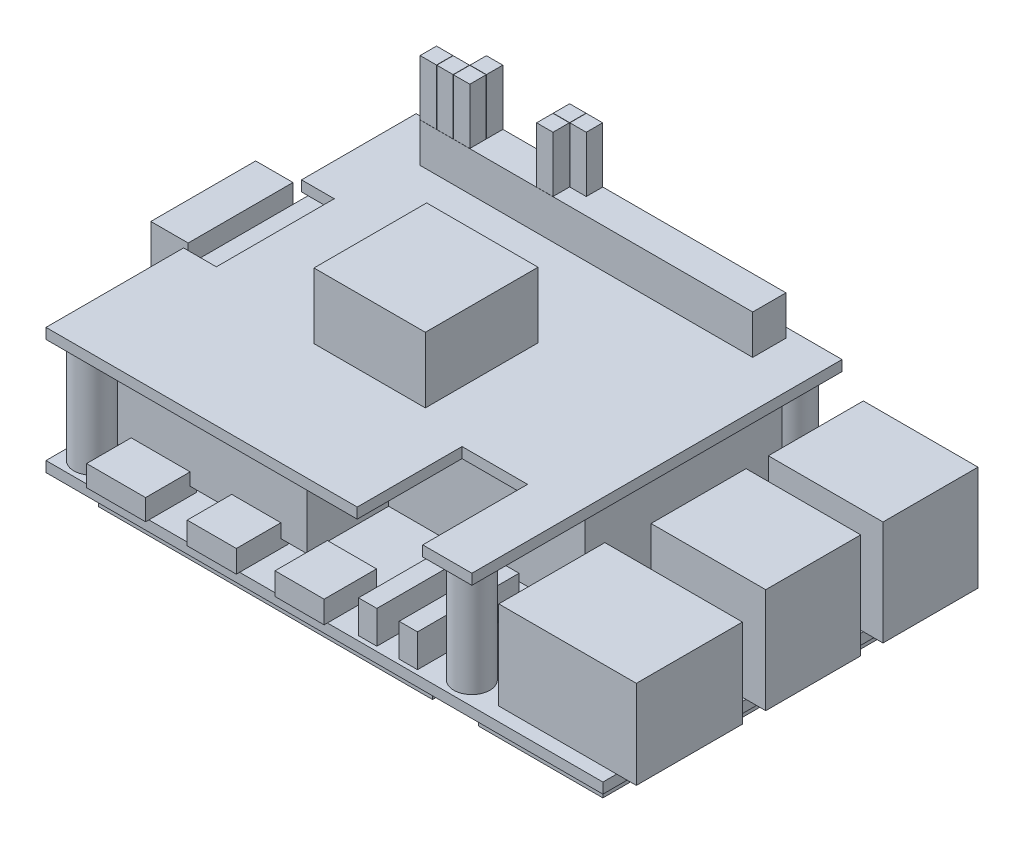
SolidWorks part; units mm, degrees
ref_plane "Front Plane" through (0, 0, 0) normal (0, 0, 1) x (1, 0, 0)
ref_plane "Top Plane" through (0, 0, 0) normal (0, 1, 0) x (1, 0, 0)
ref_plane "Right Plane" through (0, 0, 0) normal (1, 0, 0) x (0, 0, -1)
ref_plane "PZm18" through (0, -18, 0) normal (0, 1, 0) x (1, 0, 0)
sketch "Sketch1" plane through (0, -18, 0) normal (0, 1, 0) x (1, 0, 0)
  line L0 (-55, -92.5) -> (30, -92.5)
  line L1 (30, -92.5) -> (30, -36.5)
  line L2 (30, -36.5) -> (-55, -36.5)
  line L3 (-55, -36.5) -> (-55, -92.5)
extrude "Pi 5 PCB" add sketch "Sketch1" along normal blind 1.6
ref_plane "PZm19_5" through (0, -19.5, 0) normal (0, 1, 0) x (1, 0, 0)
sketch "Sketch2" plane through (0, -19.5, 0) normal (0, 1, 0) x (1, 0, 0)
  line L0 (-48, -91.5) -> (3, -91.5)
  line L1 (3, -91.5) -> (3, -37.5)
  line L2 (3, -37.5) -> (-48, -37.5)
  line L3 (-48, -37.5) -> (-48, -91.5)
extrude "Underside Parts 1" add sketch "Sketch2" along normal blind 1.5
sketch "Sketch3" plane through (0, -19.5, 0) normal (0, 1, 0) x (1, 0, 0)
  line L0 (-54, -85.5) -> (29, -85.5)
  line L1 (29, -85.5) -> (29, -43.5)
  line L2 (29, -43.5) -> (-54, -43.5)
  line L3 (-54, -43.5) -> (-54, -85.5)
extrude "Underside Parts 2" add sketch "Sketch3" along normal blind 1.5
sketch "Sketch4" plane through (0, -19.5, 0) normal (0, 1, 0) x (1, 0, 0)
  line L0 (10, -91.5) -> (29, -91.5)
  line L1 (29, -91.5) -> (29, -37.5)
  line L2 (29, -37.5) -> (10, -37.5)
  line L3 (10, -37.5) -> (10, -91.5)
extrude "Underside Parts 3" add sketch "Sketch4" along normal blind 1.5
sketch "Sketch5" plane through (0, -19.5, 0) normal (0, 1, 0) x (1, 0, 0)
  line L0 (-57.5, -70.5) -> (-41, -70.5)
  line L1 (-41, -70.5) -> (-41, -58.5)
  line L2 (-41, -58.5) -> (-57.5, -58.5)
  line L3 (-57.5, -58.5) -> (-57.5, -70.5)
extrude "microSD Card" add sketch "Sketch5" along normal blind 1.5
ref_plane "PZm15_1" through (0, -15.1, 0) normal (0, 1, 0) x (1, 0, 0)
sketch "Sketch6" plane through (0, -15.1, 0) normal (0, 1, 0) x (1, 0, 0)
  line L0 (-55, -86.2) -> (-21.5, -86.2)
  line L1 (-21.5, -86.2) -> (-21.5, -43.7)
  line L2 (-21.5, -43.7) -> (-55, -43.7)
  line L3 (-55, -43.7) -> (-55, -86.2)
extrude "Cooler Fins" add sketch "Sketch6" along normal blind 13.7
sketch "Sketch7" plane through (0, -15.1, 0) normal (0, 1, 0) x (1, 0, 0)
  line L0 (-21.5, -73.7) -> (8.5, -73.7)
  line L1 (8.5, -73.7) -> (8.5, -43.7)
  line L2 (8.5, -43.7) -> (-21.5, -43.7)
  line L3 (-21.5, -43.7) -> (-21.5, -73.7)
extrude "Cooler Fan" add sketch "Sketch7" along normal blind 13.7
ref_plane "PZm16_4" through (0, -16.4, 0) normal (0, 1, 0) x (1, 0, 0)
sketch "Sketch8" plane through (0, -16.4, 0) normal (0, 1, 0) x (1, 0, 0)
  line L0 (-47.9, -42.54) -> (2.9, -42.54)
  line L1 (2.9, -42.54) -> (2.9, -37.46)
  line L2 (2.9, -37.46) -> (-47.9, -37.46)
  line L3 (-47.9, -37.46) -> (-47.9, -42.54)
extrude "40-pin Header And Stacking Socket" add sketch "Sketch8" along normal blind 16
sketch "Sketch9" plane through (0, -16.4, 0) normal (0, 1, 0) x (1, 0, 0)
  circle A0 centre (-51.5, -89) radius 2.75
extrude "HAT Spacer 1" add sketch "Sketch9" along normal blind 16
sketch "Sketch10" plane through (0, -16.4, 0) normal (0, 1, 0) x (1, 0, 0)
  circle A0 centre (6.5, -89) radius 2.75
extrude "HAT Spacer 2" add sketch "Sketch10" along normal blind 16
sketch "Sketch11" plane through (0, -16.4, 0) normal (0, 1, 0) x (1, 0, 0)
  circle A0 centre (-51.5, -40) radius 2.75
extrude "HAT Spacer 3" add sketch "Sketch11" along normal blind 16
sketch "Sketch12" plane through (0, -16.4, 0) normal (0, 1, 0) x (1, 0, 0)
  circle A0 centre (6.5, -40) radius 2.75
extrude "HAT Spacer 4" add sketch "Sketch12" along normal blind 16
ref_plane "PZm0_4" through (0, -0.4, 0) normal (0, 1, 0) x (1, 0, 0)
sketch "Sketch13" plane through (0, -0.4, 0) normal (0, 1, 0) x (1, 0, 0)
  line L0 (-55, -92.5) -> (-7.5, -92.5)
  line L1 (-7.5, -92.5) -> (-7.5, -76.5)
  line L2 (-7.5, -76.5) -> (2.5, -76.5)
  line L3 (2.5, -76.5) -> (2.5, -92.5)
  line L4 (2.5, -92.5) -> (10, -92.5)
  line L5 (10, -92.5) -> (10, -36)
  line L6 (10, -36) -> (-55, -36)
  line L7 (-55, -36) -> (-55, -53.5)
  line L8 (-55, -53.5) -> (-50, -53.5)
  line L9 (-50, -53.5) -> (-50, -71.5)
  line L10 (-50, -71.5) -> (-55, -71.5)
  line L11 (-55, -71.5) -> (-55, -92.5)
extrude "AI HAT+ PCB" add sketch "Sketch13" along normal blind 1.6
ref_plane "PZ1_2" through (0, 1.2, 0) normal (0, 1, 0) x (1, 0, 0)
sketch "Sketch14" plane through (0, 1.2, 0) normal (0, 1, 0) x (1, 0, 0)
  line L0 (-32.4, -74.2) -> (-15.4, -74.2)
  line L1 (-15.4, -74.2) -> (-15.4, -57)
  line L2 (-15.4, -57) -> (-32.4, -57)
  line L3 (-32.4, -57) -> (-32.4, -74.2)
extrude "Hailo And Heatsink" add sketch "Sketch14" along normal blind 10
sketch "Sketch15" plane through (0, 1.2, 0) normal (0, 1, 0) x (1, 0, 0)
  line L0 (-47.9, -42.54) -> (2.9, -42.54)
  line L1 (2.9, -42.54) -> (2.9, -37.46)
  line L2 (2.9, -37.46) -> (-47.9, -37.46)
  line L3 (-47.9, -37.46) -> (-47.9, -42.54)
extrude "Stacking Pins" add sketch "Sketch15" along normal blind 6
ref_plane "PZ1_7" through (0, 1.7, 0) normal (0, 1, 0) x (1, 0, 0)
sketch "Sketch16" plane through (0, 1.7, 0) normal (0, 1, 0) x (1, 0, 0)
  line L0 (-47.88, -42.52) -> (-45.38, -42.52)
  line L1 (-45.38, -42.52) -> (-45.38, -40.02)
  line L2 (-45.38, -40.02) -> (-47.88, -40.02)
  line L3 (-47.88, -40.02) -> (-47.88, -42.52)
  line L4 (-45.34, -42.52) -> (-42.84, -42.52)
  line L5 (-42.84, -42.52) -> (-42.84, -40.02)
  line L6 (-42.84, -40.02) -> (-45.34, -40.02)
  line L7 (-45.34, -40.02) -> (-45.34, -42.52)
  line L8 (-42.8, -42.52) -> (-40.3, -42.52)
  line L9 (-40.3, -42.52) -> (-40.3, -40.02)
  line L10 (-40.3, -40.02) -> (-42.8, -40.02)
  line L11 (-42.8, -40.02) -> (-42.8, -42.52)
  line L12 (-42.8, -39.98) -> (-40.3, -39.98)
  line L13 (-40.3, -39.98) -> (-40.3, -37.48)
  line L14 (-40.3, -37.48) -> (-42.8, -37.48)
  line L15 (-42.8, -37.48) -> (-42.8, -39.98)
  line L16 (-30.1, -42.52) -> (-27.6, -42.52)
  line L17 (-27.6, -42.52) -> (-27.6, -40.02)
  line L18 (-27.6, -40.02) -> (-30.1, -40.02)
  line L19 (-30.1, -40.02) -> (-30.1, -42.52)
  line L20 (-30.1, -39.98) -> (-27.6, -39.98)
  line L21 (-27.6, -39.98) -> (-27.6, -37.48)
  line L22 (-27.6, -37.48) -> (-30.1, -37.48)
  line L23 (-30.1, -37.48) -> (-30.1, -39.98)
  line L24 (-27.56, -39.98) -> (-25.06, -39.98)
  line L25 (-25.06, -39.98) -> (-25.06, -37.48)
  line L26 (-25.06, -37.48) -> (-27.56, -37.48)
  line L27 (-27.56, -37.48) -> (-27.56, -39.98)
extrude "Dupont Housings" add sketch "Sketch16" along normal blind 14
ref_plane "PZm17_4" through (0, -17.4, 0) normal (0, 1, 0) x (1, 0, 0)
sketch "Sketch17" plane through (0, -17.4, 0) normal (0, 1, 0) x (1, 0, 0)
  line L0 (-61, -70.5) -> (-55.3, -70.5)
  line L1 (-55.3, -70.5) -> (-55.3, -54.5)
  line L2 (-55.3, -54.5) -> (-61, -54.5)
  line L3 (-61, -54.5) -> (-61, -70.5)
extrude "PCIe Flat Cable Loop" add sketch "Sketch17" along normal blind 18.6
sketch "Sketch18" plane through (0, -16.4, 0) normal (0, 1, 0) x (1, 0, 0)
  line L0 (12, -90.4) -> (33, -90.4)
  line L1 (33, -90.4) -> (33, -74.2)
  line L2 (33, -74.2) -> (12, -74.2)
  line L3 (12, -74.2) -> (12, -90.4)
extrude "Ethernet" add sketch "Sketch18" along normal blind 13.5
sketch "Sketch19" plane through (0, -16.4, 0) normal (0, 1, 0) x (1, 0, 0)
  line L0 (15.5, -70.65) -> (33, -70.65)
  line L1 (33, -70.65) -> (33, -56.15)
  line L2 (33, -56.15) -> (15.5, -56.15)
  line L3 (15.5, -56.15) -> (15.5, -70.65)
  line L4 (15.5, -52.75) -> (33, -52.75)
  line L5 (33, -52.75) -> (33, -38.25)
  line L6 (33, -38.25) -> (15.5, -38.25)
  line L7 (15.5, -38.25) -> (15.5, -52.75)
extrude "USB-A Stacks" add sketch "Sketch19" along normal blind 16
sketch "Sketch20" plane through (0, -16.4, 0) normal (0, 1, 0) x (1, 0, 0)
  line L0 (-48.3, -93) -> (-39.3, -93)
  line L1 (-39.3, -93) -> (-39.3, -85.2)
  line L2 (-39.3, -85.2) -> (-48.3, -85.2)
  line L3 (-48.3, -85.2) -> (-48.3, -93)
extrude "USB-C" add sketch "Sketch20" along normal blind 3.2
sketch "Sketch21" plane through (0, -16.4, 0) normal (0, 1, 0) x (1, 0, 0)
  line L0 (-32.95, -93) -> (-25.45, -93)
  line L1 (-25.45, -93) -> (-25.45, -85)
  line L2 (-25.45, -85) -> (-32.95, -85)
  line L3 (-32.95, -85) -> (-32.95, -93)
  line L4 (-19.55, -93) -> (-12.05, -93)
  line L5 (-12.05, -93) -> (-12.05, -85)
  line L6 (-12.05, -85) -> (-19.55, -85)
  line L7 (-19.55, -85) -> (-19.55, -93)
extrude "Micro-HDMI" add sketch "Sketch21" along normal blind 3.4
sketch "Sketch22" plane through (0, -16.4, 0) normal (0, 1, 0) x (1, 0, 0)
  line L0 (-8, -91.8) -> (-5.2, -91.8)
  line L1 (-5.2, -91.8) -> (-5.2, -76.3)
  line L2 (-5.2, -76.3) -> (-8, -76.3)
  line L3 (-8, -76.3) -> (-8, -91.8)
  line L4 (-1.8, -91.8) -> (1, -91.8)
  line L5 (1, -91.8) -> (1, -76.3)
  line L6 (1, -76.3) -> (-1.8, -76.3)
  line L7 (-1.8, -76.3) -> (-1.8, -91.8)
extrude "CAM-DISP Connectors" add sketch "Sketch22" along normal blind 5
